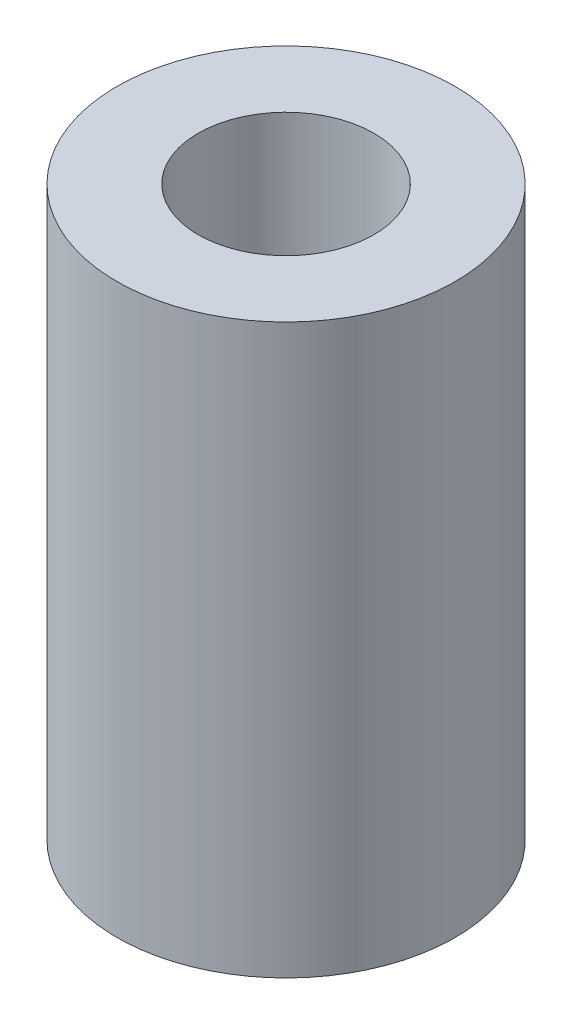
SolidWorks part; units mm, degrees
ref_plane "Front Plane" through (0, 0, 0) normal (0, 0, 1) x (1, 0, 0)
ref_plane "Top Plane" through (0, 0, 0) normal (0, 1, 0) x (1, 0, 0)
ref_plane "Right Plane" through (0, 0, 0) normal (1, 0, 0) x (0, 0, -1)
sketch "Sketch1" plane through (0, 0, 0) normal (0, 1, 0) x (1, 0, 0)
  circle A1 centre (0, 0) radius 6.25
  circle A2 centre (0, 0) radius 3.25
  dimension "D1" = 12.5
  dimension "D2" = 6.5
extrude "Boss-Extrude1" add sketch "Sketch1" along normal blind 21
